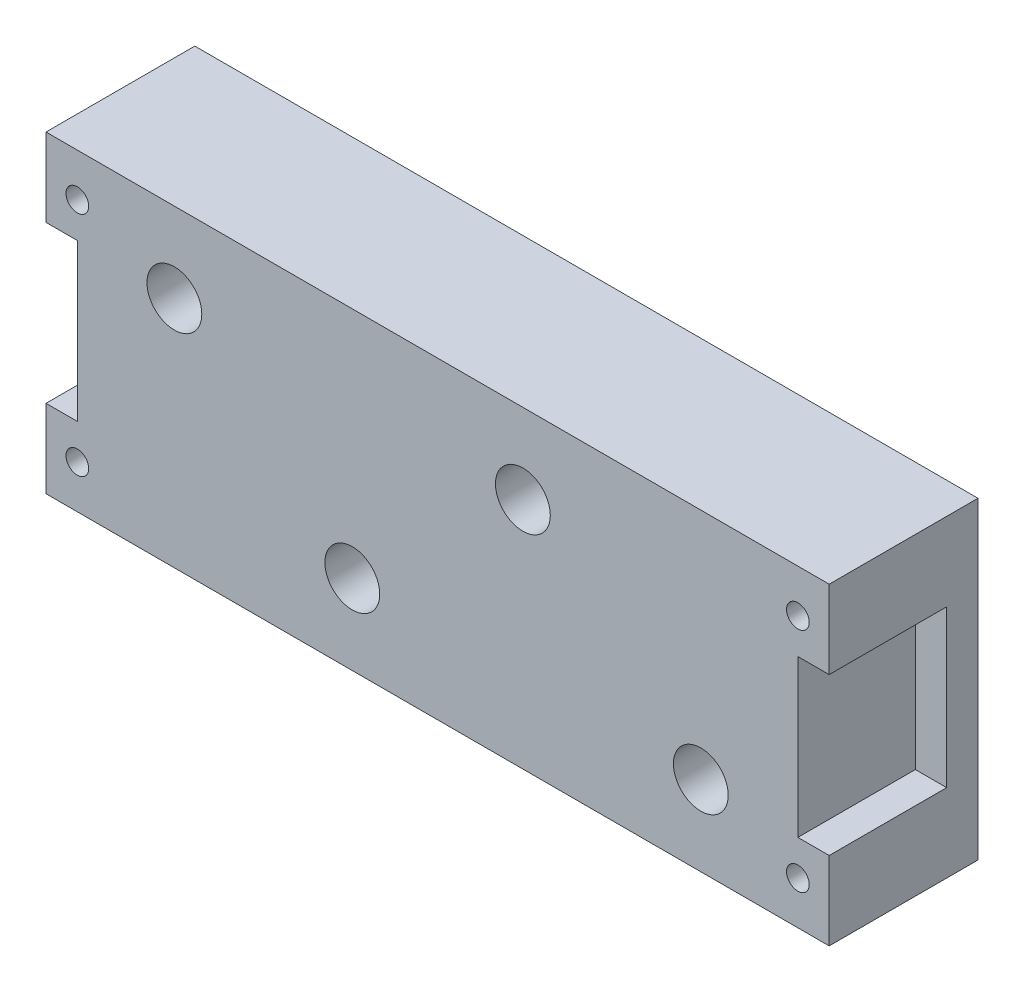
SolidWorks part; units mm, degrees
material "ABS PC"
ref_plane "Front Plane" through (0, 0, 0) normal (0, 0, 1) x (1, 0, 0)
ref_plane "Top Plane" through (0, 0, 0) normal (0, 1, 0) x (1, 0, 0)
ref_plane "Right Plane" through (0, 0, 0) normal (1, 0, 0) x (0, 0, -1)
sketch "Sketch1" plane through (0, 0, 0) normal (0, 0, 1) x (1, 0, 0)
  line L1 (-33.75, 21.5625) -> (66.25, 21.5625)
  line L2 (-33.75, 21.5625) -> (-33.75, -18.4375)
  line L3 (-33.75, -18.4375) -> (66.25, -18.4375)
  line L4 (66.25, 21.5625) -> (66.25, -18.4375)
  dimension "D1" = 100
  dimension "D2" = 40
extrude "Boss-Extrude1" add sketch "Sketch1" along normal blind 38
sketch "Sketch2" plane through (0, 0, 0) normal (0, 0, -1) x (-1, 0, 0)
  line L0 (-66.25, -18.4375) -> (-66.25, 21.5625) construction
  line L1 (-58.25, 18.5625) -> (-18.75, 18.5625)
  line L2 (-58.25, 18.5625) -> (-58.25, -15.4375)
  line L3 (-58.25, -15.4375) -> (-18.75, -15.4375)
  line L4 (-18.75, 18.5625) -> (-18.75, -15.4375)
  line L5 (-13.75, 18.5625) -> (25.75, 18.5625)
  line L6 (-13.75, 18.5625) -> (-13.75, -15.4375)
  line L7 (-13.75, -15.4375) -> (25.75, -15.4375)
  line L8 (25.75, 18.5625) -> (25.75, -15.4375)
  line L9 (33.75, 21.5625) -> (33.75, -18.4375) construction
  line L10 (-66.25, 21.5625) -> (33.75, 21.5625) construction
  line L11 (33.75, -18.4375) -> (-66.25, -18.4375) construction
  dimension "D1" = 8
  dimension "D2" = 8
  dimension "D3" = 5
  dimension "D4" = 3
  dimension "D5" = 3
  dimension "D6" = 3
  dimension "D7" = 3
  dimension "D8" = 39.5
  dimension "D9" = 39.5
extrude "Cut-Extrude2" cut sketch "Sketch2" against normal blind 21 from offset 12 offset against normal yes
sketch "Sketch3" plane through (-3.3623, 0, 0) normal (0, 0, -1) x (-1, 0, 0)
  arc A0 (-55.6418, 7.0775) -> (16.2528, 4.0018) centre (-18.1567, 41.487) ccw construction
  arc A1 (-61.5934, 1.6143) -> (21.716, -1.9497) centre (-18.1567, 41.487) ccw
  arc A2 (-49.6903, 12.5407) -> (10.7896, 9.9533) centre (-18.1567, 41.487) ccw
  arc A3 (-49.6903, 12.5407) -> (-61.5934, 1.6143) centre (-55.6418, 7.0775) ccw
  arc A4 (21.716, -1.9497) -> (10.7896, 9.9533) centre (16.2528, 4.0018) ccw
  point P3 (-20.3315, -9.3502)
extrude "Cut-Extrude3" cut sketch "Sketch3" against normal blind 9 contours A2 A4 A1 A3
sketch "Sketch4" plane through (0, 0, 0) normal (0, 0, -1) x (-1, 0, 0)
  line L0 (-66.25, -18.4375) -> (-66.25, 21.5625) construction
  line L1 (33.75, 21.5625) -> (33.75, -18.4375) construction
  line L2 (-66.25, 21.5625) -> (33.75, 21.5625) construction
  line L3 (33.75, -18.4375) -> (-66.25, -18.4375) construction
  circle A0 centre (-62.25, 16.0625) radius 1.45
  circle A1 centre (-62.25, -12.9375) radius 1.45
  circle A2 centre (29.75, 16.0625) radius 1.45
  circle A3 centre (29.75, -12.9375) radius 1.45
  point P8 (0, 0)
  dimension "D1" = 4
  dimension "D2" = 4
  dimension "D3" = 5.5
  dimension "D4" = 5.5
extrude "Cut-Extrude4" cut sketch "Sketch4" against normal up to next
sketch "Sketch5" plane through (0, 21.5625, 0) normal (0, 1, 0) x (1, 0, 0)
  line L0 (-33.75, -38) -> (-33.75, 0) construction
  line L1 (66.25, 0) -> (-33.75, 0)
  line L2 (66.25, 0) -> (66.25, -19)
  line L3 (66.25, -19) -> (-33.75, -19)
  line L4 (-33.75, 0) -> (-33.75, -19)
extrude "Cut-Extrude5" cut sketch "Sketch5" against normal through all
fillet "Fillet1" radius 0.5 8 edges at (18.75, 18.5625, 26) (58.25, 18.5625, 26) (58.25, -15.4375, 26) (18.75, -15.4375, 26) (13.75, -15.4375, 26) (13.75, 18.5625, 26) (-25.75, 18.5625, 26) (-25.75, -15.4375, 26)
sketch "Sketch8" plane through (0, 0, 33) normal (0, 0, -1) x (-1, 0, 0)
  line L8 (-18.25, -14.9375) -> (-18.25, 18.0625)
  line L9 (-19.25, 19.0625) -> (-57.75, 19.0625)
  line L10 (-58.75, 18.0625) -> (-58.75, -14.9375)
  line L11 (-57.75, -15.9375) -> (-19.25, -15.9375)
  line L12 (-18.25, -14.9375) -> (-18.25, 18.0625)
  line L13 (-19.25, 19.0625) -> (-57.75, 19.0625)
  line L14 (-58.75, 18.0625) -> (-58.75, -14.9375)
  line L15 (-57.75, -15.9375) -> (-19.25, -15.9375)
  arc A8 (-18.25, 18.0625) -> (-19.25, 19.0625) centre (-19.25, 18.0625) ccw
  arc A9 (-57.75, 19.0625) -> (-58.75, 18.0625) centre (-57.75, 18.0625) ccw
  arc A10 (-58.75, -14.9375) -> (-57.75, -15.9375) centre (-57.75, -14.9375) ccw
  arc A11 (-19.25, -15.9375) -> (-18.25, -14.9375) centre (-19.25, -14.9375) ccw
  arc A12 (-18.25, 18.0625) -> (-19.25, 19.0625) centre (-19.25, 18.0625) ccw
  arc A13 (-57.75, 19.0625) -> (-58.75, 18.0625) centre (-57.75, 18.0625) ccw
  arc A14 (-58.75, -14.9375) -> (-57.75, -15.9375) centre (-57.75, -14.9375) ccw
  arc A15 (-19.25, -15.9375) -> (-18.25, -14.9375) centre (-19.25, -14.9375) ccw
  dimension "D1" = 0.5
sketch "Sketch9" plane through (0, 0, 33) normal (0, 0, -1) x (-1, 0, 0)
  line L8 (-14.25, 18.0625) -> (-14.25, -14.9375)
  line L9 (-13.25, -15.9375) -> (25.25, -15.9375)
  line L10 (26.25, -14.9375) -> (26.25, 18.0625)
  line L11 (25.25, 19.0625) -> (-13.25, 19.0625)
  line L12 (-14.25, 18.0625) -> (-14.25, -14.9375)
  line L13 (-13.25, -15.9375) -> (25.25, -15.9375)
  line L14 (26.25, -14.9375) -> (26.25, 18.0625)
  line L15 (25.25, 19.0625) -> (-13.25, 19.0625)
  arc A8 (-14.25, -14.9375) -> (-13.25, -15.9375) centre (-13.25, -14.9375) ccw
  arc A9 (25.25, -15.9375) -> (26.25, -14.9375) centre (25.25, -14.9375) ccw
  arc A10 (26.25, 18.0625) -> (25.25, 19.0625) centre (25.25, 18.0625) ccw
  arc A11 (-13.25, 19.0625) -> (-14.25, 18.0625) centre (-13.25, 18.0625) ccw
  arc A12 (-14.25, -14.9375) -> (-13.25, -15.9375) centre (-13.25, -14.9375) ccw
  arc A13 (25.25, -15.9375) -> (26.25, -14.9375) centre (25.25, -14.9375) ccw
  arc A14 (26.25, 18.0625) -> (25.25, 19.0625) centre (25.25, 18.0625) ccw
  arc A15 (-13.25, 19.0625) -> (-14.25, 18.0625) centre (-13.25, 18.0625) ccw
  dimension "D1" = 0.5
sketch "Sketch10" plane through (0, 0, 33) normal (0, 0, -1) x (-1, 0, 0)
  line L0 (-13.9571, -15.6446) -> (25.9571, 18.7696) construction
  line L1 (-58.4571, -15.6446) -> (-18.5429, 18.7696) construction
  line L2 (-27.1396, 11.3575) -> (-18.5429, 18.7696) construction
  line L3 (-27.1396, 11.3575) -> (-27.1396, 18.5625) construction
  line L4 (-19.25, 18.5625) -> (-57.75, 18.5625) construction
  line L5 (-49.8604, -8.2325) -> (-49.8604, -15.4375) construction
  line L6 (-57.75, -15.4375) -> (-19.25, -15.4375) construction
  circle A0 centre (-49.8604, -8.2325) radius 3.5
  circle A1 centre (-27.1396, 11.3575) radius 3.5
  circle A2 centre (-5.3604, -8.2325) radius 3.5
  circle A3 centre (17.3604, 11.3575) radius 3.5
  arc A4 (-14.25, -14.9375) -> (-13.25, -15.9375) centre (-13.25, -14.9375) ccw construction
  arc A5 (26.25, 18.0625) -> (25.25, 19.0625) centre (25.25, 18.0625) ccw construction
  arc A6 (-58.75, -14.9375) -> (-57.75, -15.9375) centre (-57.75, -14.9375) ccw construction
  arc A7 (-18.25, 18.0625) -> (-19.25, 19.0625) centre (-19.25, 18.0625) ccw construction
  point P24 (0, 0)
  point P31 (0, 0)
  dimension "D1" = 30
  dimension "D2" = 30
  dimension "D3" = 7
extrude "Cut-Extrude11" cut sketch "Sketch10" against normal up to next
sketch "Sketch11" plane through (0, 0, 38) normal (0, 0, 1) x (1, 0, 0)
  line L0 (-33.75, 21.5625) -> (-33.75, -18.4375) construction
  line L1 (-33.75, 11.5625) -> (-29.75, 11.5625)
  line L2 (-33.75, 11.5625) -> (-33.75, -8.4375)
  line L3 (-33.75, -8.4375) -> (-29.75, -8.4375)
  line L4 (-29.75, 11.5625) -> (-29.75, -8.4375)
  line L5 (66.25, -18.4375) -> (66.25, 21.5625) construction
  line L6 (66.25, 11.5625) -> (62.25, 11.5625)
  line L7 (66.25, 11.5625) -> (66.25, -8.4375)
  line L8 (66.25, -8.4375) -> (62.25, -8.4375)
  line L9 (62.25, 11.5625) -> (62.25, -8.4375)
  line L10 (66.25, 21.5625) -> (-33.75, 21.5625) construction
  dimension "D1" = 4
  dimension "D2" = 4
  dimension "D3" = 20
  dimension "D4" = 20
  dimension "D5" = 10
  dimension "D6" = 10
extrude "Cut-Extrude12" cut sketch "Sketch11" against normal blind 15
